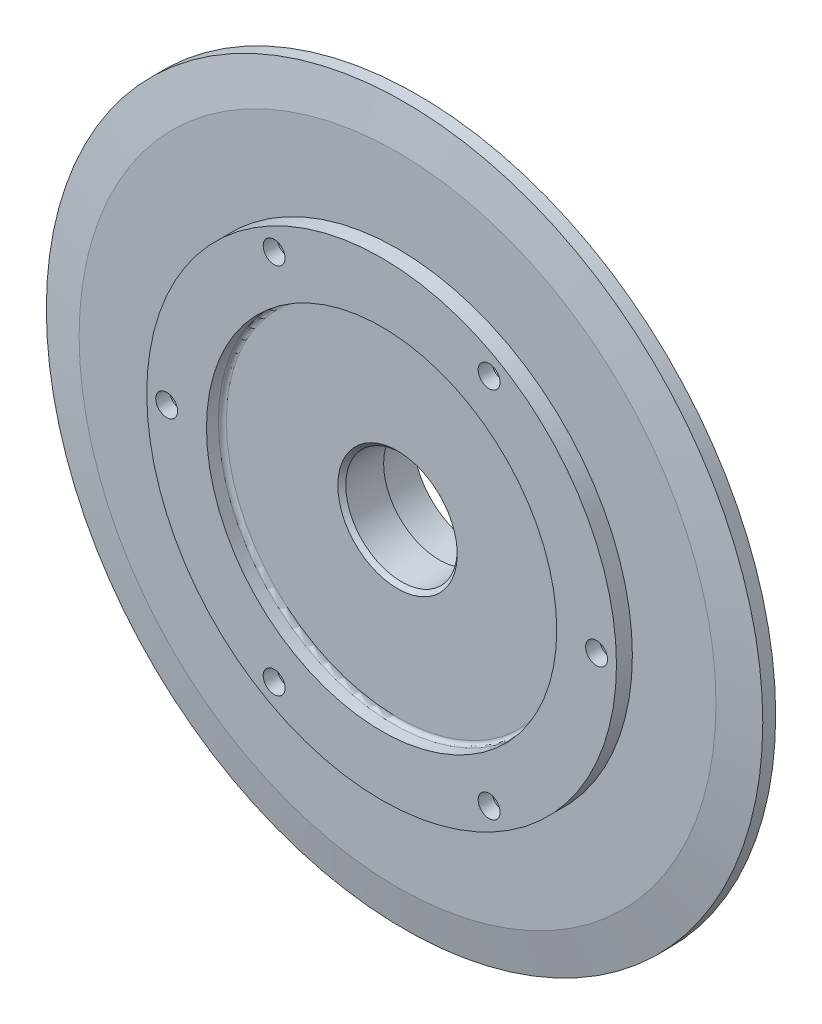
SolidWorks part; units mm, degrees
ref_plane "前视基准面" through (0, 0, 0) normal (0, 0, 1) x (1, 0, 0)
ref_plane "上视基准面" through (0, 0, 0) normal (0, 1, 0) x (1, 0, 0)
ref_plane "右视基准面" through (0, 0, 0) normal (1, 0, 0) x (0, 0, -1)
sketch "草图1" plane through (0, 0, 0) normal (1, 0, 0) x (0, 0, -1)
  line L0 (0, 0) -> (0, 118)
  line L1 (0, 118) -> (8, 118)
  line L2 (8, 118) -> (8, 160)
  line L3 (8, 160) -> (11.5265, 180)
  line L4 (11.5265, 180) -> (18, 180)
  line L5 (18, 180) -> (18, 45)
  line L6 (18, 45) -> (21, 45)
  line L7 (21, 45) -> (21, 40)
  line L8 (21, 40) -> (47, 40)
  line L9 (47, 40) -> (47, 0)
  line L10 (55, 0) -> (-55, 0) construction
  line L11 (47, 0) -> (0, 0) construction
  line L13 (0, 0) -> (47, 0)
  dimension "D1" = 10
  dimension "D2" = 20
  dimension "D3" = 236
  dimension "D4" = 360
  dimension "D5" = 90
  dimension "D6" = 80
  dimension "D7" = 26
  dimension "D8" = 18
  dimension "D9" = 10
  dimension "D10" = 47
revolve "旋转1" add sketch "草图1" angle 360 about L11
sketch "草图2" plane through (0, 0, 0) normal (1, 0, 0) x (0, 0, -1)
  line L0 (0, 0) -> (0, 88)
  line L1 (0, 198) -> (0, -198) construction
  line L2 (0, 88) -> (8, 88)
  line L3 (8, 88) -> (8, 28)
  line L4 (8, 28) -> (29, 28)
  line L5 (29, 28) -> (29, 31)
  line L6 (29, 31) -> (47, 31)
  line L7 (47, -40) -> (47, 40) construction
  line L8 (47, 31) -> (47, 0)
  line L9 (47, 0) -> (0, 0) construction
  line L10 (0, 0) -> (47, 0)
  dimension "D1" = 176
  dimension "D2" = 56
  dimension "D3" = 62
  dimension "D4" = 18
  dimension "D5" = 21
revolve "切除-旋转1" cut sketch "草图2" angle 360 about L9
sketch "草图3" plane through (0, 0, -18) normal (0, 0, -1) x (-1, 0, 0)
  circle A0 centre (0, 0) radius 77
  circle A1 centre (0, 0) radius 70
  dimension "D1" = 154
  dimension "D2" = 140
extrude "切除-拉伸1" cut sketch "草图3" against normal blind 4
sketch "草图4" plane through (0, 0, -18) normal (0, 0, -1) x (-1, 0, 0)
  circle A0 centre (0, 0) radius 108 construction
  point P3 (108, 0)
  point P7 (54, -93.5307)
  point P8 (-54, -93.5307)
  point P9 (-108, 0)
  point P10 (-54, 93.5307)
  point P11 (54, 93.5307)
  dimension "D1" = 216
  dimension "D2" = 6
hole_wizard "孔1" positions "草图4" profile "草图5" legacy end condition up to next
sketch "草图5" plane through (-54, 93.5307, -18) normal (1, 0, 0) x (0, 1, 0)
  line L0 (0, 0) -> (0, 18)
  line L1 (0, 18) -> (5.5, 18)
  line L2 (5.5, 18) -> (5.5, 11)
  line L3 (5.5, 11) -> (8.5, 11)
  line L4 (8.5, 11) -> (8.5, 0)
  line L5 (8.5, 0) -> (0, 0)
  line L6 (0, 110) -> (0, -10) construction
  dimension "直径" = 11
  dimension "深度" = 18
  dimension "柱坑直径" = 17
  dimension "柱坑深度" = 11
fillet "圆角1" radius 2 1 edges at (-88, 0, -8)
chamfer "倒角1" distance 2 angle 45 1 edges at (-28, 0, -8)
